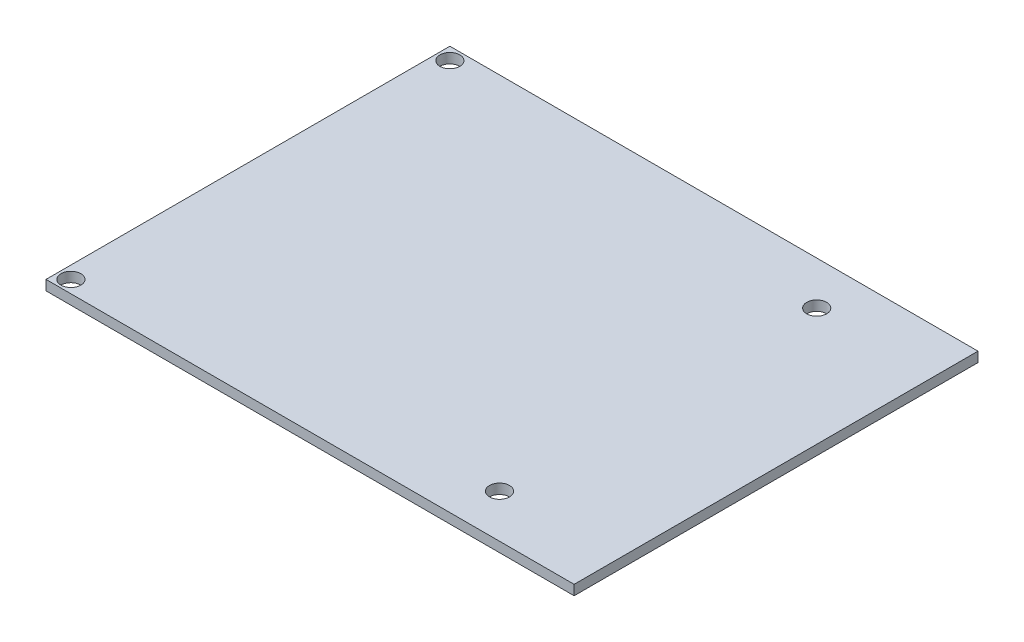
SolidWorks part; units mm, degrees
material "ABS"
ref_plane "Front Plane" through (0, 0, 0) normal (0, 0, 1) x (1, 0, 0)
ref_plane "Top Plane" through (0, 0, 0) normal (0, 1, 0) x (1, 0, 0)
ref_plane "Right Plane" through (0, 0, 0) normal (1, 0, 0) x (0, 0, -1)
sketch "Sketch1" plane through (0, 0, 0) normal (0, 1, 0) x (1, 0, 0)
  line L0 (-42.5, 0) -> (42.5, 0) construction
  line L1 (-42.5, -32.5) -> (42.5, -32.5)
  line L2 (-42.5, -32.5) -> (-42.5, 32.5)
  line L3 (-42.5, 32.5) -> (42.5, 32.5)
  line L4 (42.5, -32.5) -> (42.5, 32.5)
  line L5 (-42.5, -32.5) -> (42.5, 32.5) construction
  line L6 (-42.5, 32.5) -> (42.5, -32.5) construction
  circle A0 centre (-40.495, 30.495) radius 1.605
  circle A2 centre (23.515, 25.525) radius 1.605
  circle A3 centre (23.515, -25.525) radius 1.605
  circle A4 centre (-40.495, -30.495) radius 1.605
  point P0 (0, 0)
  dimension "D3" = 3.21
  dimension "D4" = 3.21
  dimension "D5" = 2.005
  dimension "D6" = 2.005
  dimension "D7" = 18.985
  dimension "D8" = 6.975
  dimension "D1" = 85
  dimension "D2" = 65
  dimension "D9" = 64.01
  dimension "D10" = 60.99
  dimension "D11" = 51.05
  dimension "D12" = 4.97
extrude "Boss-Extrude1" add sketch "Sketch1" along normal blind 1.6
